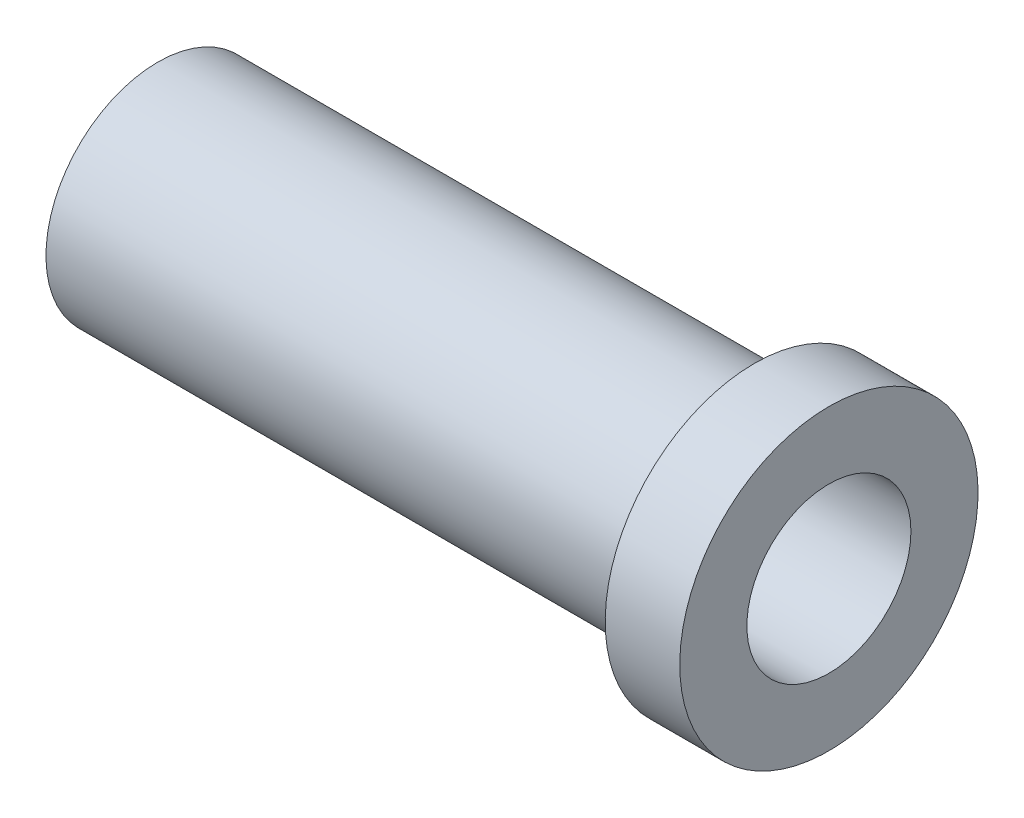
SolidWorks part; units mm, degrees
ref_plane "Front Plane" through (0, 0, 0) normal (0, 0, 1) x (1, 0, 0)
ref_plane "Top Plane" through (0, 0, 0) normal (0, 1, 0) x (1, 0, 0)
ref_plane "Right Plane" through (0, 0, 0) normal (1, 0, 0) x (0, 0, -1)
sketch "Sketch1" plane through (0, 0, 0) normal (0, 0, 1) x (1, 0, 0)
  line L0 (0, 0) -> (0, 7.5)
  line L1 (0, 7.5) -> (40, 7.5)
  line L2 (40, 7.5) -> (40, 10)
  line L3 (40, 10) -> (45, 10)
  line L4 (45, 10) -> (45, 0)
  line L5 (45, 0) -> (0, 0) construction
  line L6 (0, 0) -> (45, 0)
  dimension "D1" = 40
  dimension "D2" = 5
  dimension "D3" = 10
  dimension "D4" = 7.5
revolve "Revolve1" add sketch "Sketch1" angle 360 about L5
hole_wizard "Ø1.0mm Dowel Hole2" positions "3DSketch2" profile "Sketch3" hole size "Ø1.0" standard "ANSI Metric" end condition through all
sketch3d "3DSketch2"
  line L0 (40, 0, 0) -> (45, 0, 0) construction
  point P0 (45, 0, 0)
sketch "Sketch3" plane through (45, 0, 0) normal (0, 1, 0) x (0, 0, -1)
  line L0 (0, 0) -> (0, 45)
  line L1 (0, 45) -> (5.5, 45)
  line L2 (5.5, 45) -> (5.5, 0)
  line L5 (5.5, 0) -> (0, 0)
  line L11 (0, -6.35) -> (0, 107.95) construction
  dimension "Thru Hole Dia." = 11
  dimension "Thru Hole Depth" = 45
